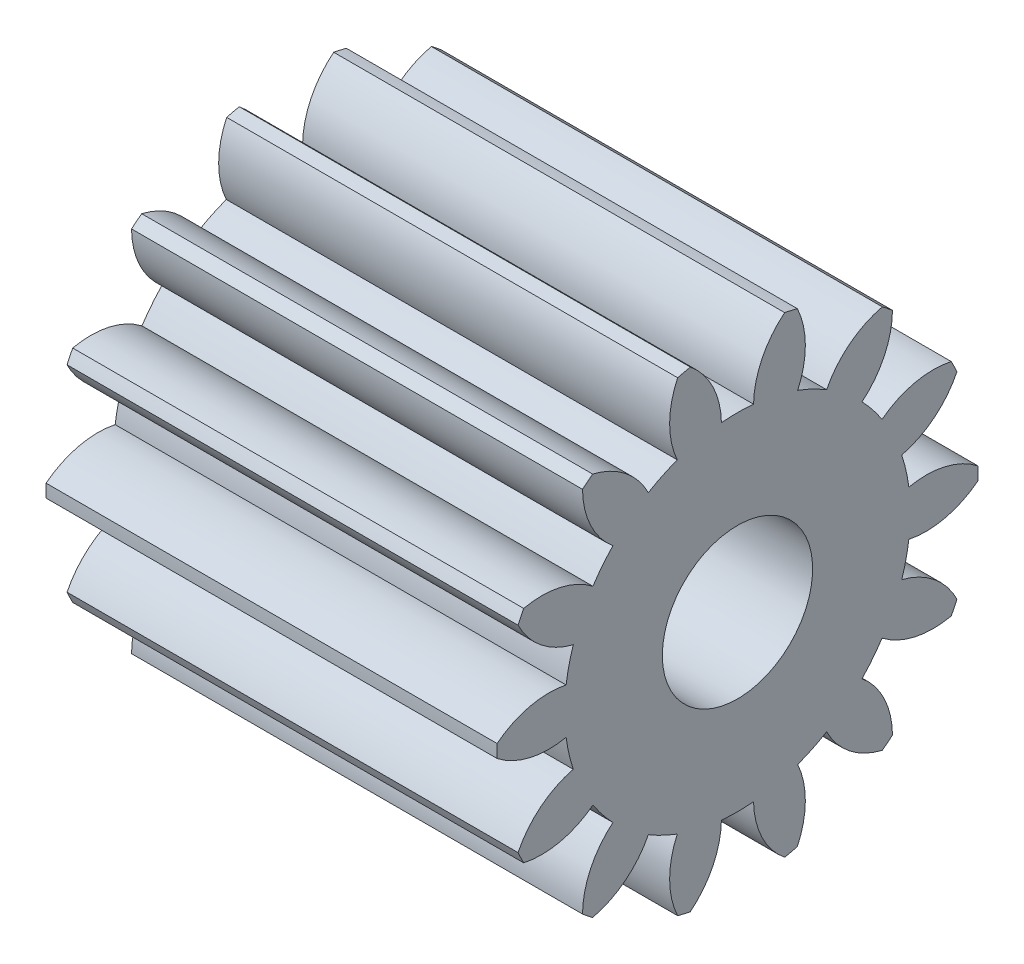
SolidWorks part; units mm, degrees
ref_plane "Plane1" through (0, 0, 0) normal (0, 0, 1) x (1, 0, 0)
ref_plane "Plane2" through (0, 0, 0) normal (0, 1, 0) x (1, 0, 0)
ref_plane "Plane3" through (0, 0, 0) normal (1, 0, 0) x (0, 0, -1)
sketch "HoldingSke" plane through (0, 0, 0) normal (0, 1, 0) x (1, 0, 0)
  line L0 (0, 0) -> (0.4851, -0.121)
  line L1 (-15, 0) -> (100, 0) construction
  line L2 (0, 0) -> (-2.1039, 2.3779)
  line L3 (0, 0) -> (-11.863, 4.5341)
  line L4 (0, 0) -> (8.3795, 2.0892)
  line L5 (0, 0) -> (-46.8476, -17.4728)
  line L6 (0, 0) -> (-24.8689, -16.7791)
  line L7 (-2.1039, 2.3779) -> (8.6586, 51.2059)
  line L8 (-76.2, 54.61) -> (-74.4, 54.61)
  line L9 (-71.009, 38.7566) -> (-53.1078, 45.2721)
  line L10 (-76.2, 71.12) -> (104.1128, 71.12)
  line L11 (0, 0) -> (-30, 0)
  line L12 (-76.2, 101.6) -> (-76.133, 101.6)
  line L13 (24.9733, 27.94) -> (52.9518, 28.4284)
  line L14 (24.9733, 27.94) -> (24.9743, 27.94)
  line L15 (24.9733, 27.94) -> (100.4006, 29.5858)
  line L16 (-63.627, -2) -> (-12.827, -2)
  circle A0 centre (0, 0) radius 5
  circle A1 centre (0, 0) radius 11.499
  circle A2 centre (0, 0) radius 37.5
  circle A3 centre (0, 0) radius 5
  dimension "MHD" = 22.998
  dimension "Hub_dia" = 75
  dimension "Bore" = 10
  dimension "MBD" = 10
  dimension "Num_teeth" = 14
  dimension "Pitch" = 0.5
  dimension "Overall_len" = 50
  dimension "Show_teeth" = 14
  dimension "Thickness" = 30
  dimension "OAL" = 50.0001
  dimension "T_dim" = 1.8
  dimension "Ap" = 20
  dimension "H" = 19.05
  dimension "Pitch_radius" = 180.3128
  dimension "Width" = 30
  dimension "Backlash" = 0.067
  dimension "Addendum_fac" = 1
  dimension "Dedendum_fac" = 1.25
  dimension "Clearance_fac" = 0.25
  dimension "Dedendum_add" = 0.001
  dimension "Module" = 2
sketch "BasProSke" plane through (0, 0, 0) normal (0, 1, 0) x (1, 0, 0)
  line L0 (-10, 0) -> (60, 0) construction
  line L1 (0, 0) -> (0, 16)
  line L2 (0, 0) -> (30, 0)
  line L3 (30, 0) -> (30, 16)
  line L4 (30, 16) -> (0, 16)
  dimension "Thickness" = 30
  dimension "Diameter" = 32
revolve "Base-Revolve" add sketch "BasProSke" angle 360 about L0
sketch "TooCutSke" plane through (0, 0, 0) normal (1, 0, 0) x (0, 0, -1)
  line L1 (0, 0) -> (0, 107) construction
  line L2 (0, 0) -> (-1.6846, 13.8983) construction
  line L3 (0, 0) -> (-6.1971, 27.1511) construction
  line L4 (-1.6846, 13.8983) -> (-3.0985, 13.5756) construction
  arc A0 (1.0679, 11.4493) -> (-1.0679, 11.4493) centre (0, 0) ccw
  arc A1 (3.1634, 15.7101) -> (-3.1634, 15.7101) centre (0, 0) ccw
  circle A2 centre (0, 0) radius 14 construction
  circle A3 centre (0, 0) radius 13.1557 construction
  arc A4 (-1.0679, 11.4493) -> (-3.1634, 15.7101) centre (-6.6668, 11.3413) ccw
  arc A5 (3.1634, 15.7101) -> (1.0679, 11.4493) centre (6.6668, 11.3413) ccw
  dimension "Root_dia" = 22.998
  dimension "Overcut_dia" = 32.0508
  dimension "Pitch_dia" = 28
  dimension "Base_dia" = 26.3114
  dimension "Flank_rad" = 5.6
  dimension "Half_ang" = 12.857
  dimension "Half_CT" = 1.4503
extrude "ToothCut" cut sketch "TooCutSke" along normal through all
fillet "Breaks" [suppressed] radius 0.04
fillet "RootFillets" [suppressed] radius 0.501
pattern_circular "TeethCuts" count 14 every 25.714 about axis through (-10, 0, 0) along (1, 0, 0) of "ToothCut", "RootFillets", "Breaks"
sketch "HubNeaOneSke" plane through (0, 0, 0) normal (-1, 0, 0) x (0, 0, 1)
  circle A0 centre (0, 0) radius 11.499
  dimension "Diameter" = 22.998
extrude "HubNearOne" [suppressed] add sketch "HubNeaOneSke" along normal blind 20.0001
sketch "HubNeaBotSke" plane through (0, 0, 0) normal (-1, 0, 0) x (0, 0, 1)
  circle A0 centre (0, 0) radius 11.499
  dimension "Diameter" = 22.998
extrude "HubNearBoth" [suppressed] add sketch "HubNeaBotSke" along normal blind 10
ref_plane "FarPln" through (30, 0, 0) normal (1, 0, 0) x (0, 0, -1)
sketch "HubFarSke" plane through (30, 0, 0) normal (1, 0, 0) x (0, 0, -1)
  circle A0 centre (0, 0) radius 11.499
  dimension "Diameter" = 22.998
extrude "HubFar" [suppressed] add sketch "HubFarSke" along normal blind 10
sketch "BorSke" plane through (0, 0, 0) normal (1, 0, 0) x (0, 0, -1)
  circle A0 centre (0, 0) radius 5
  dimension "Diameter" = 10
extrude "Bore" cut sketch "BorSke" along normal mid plane 100.0001
sketch "KeySke" plane through (0, 0, 0) normal (1, 0, 0) x (0, 0, -1)
  line L0 (-2, 0) -> (-2, 6.8)
  line L1 (-2, 6.8) -> (2, 6.8)
  line L2 (2, 6.8) -> (2, 0)
  line L3 (0, 0) -> (0, 34) construction
  line L4 (-2, 0) -> (2, 0)
  dimension "Offset" = 6.8
  dimension "Width" = 4
extrude "Keyway" [suppressed] cut sketch "KeySke" along normal mid plane 100.0001
pattern_circular "Keyway2" [suppressed] count 2 every 90 about axis through (-10, 0, 0) along (1, 0, 0)
equation "' \"Module@HoldingSke\" = 6.35"
equation "' \"Num_teeth@HoldingSke\" = 12"
equation "' \"Ap@HoldingSke\" =  20"
equation "' \"Ap@HoldingSke\" = 20"
equation "' \"Width@HoldingSke\" = 0.5 * 25.4"
equation "' \"Hub_dia@HoldingSke\"= 1 * 25.4"
equation "' \"Hub_dia@HoldingSke\" = 1 * 25.4"
equation "' \"Overall_len@HoldingSke\" = 1.0 * 25.4"
equation "' \"Bore@HoldingSke\" = 0.75 * 25.4"
equation "' \"T_dim@HoldingSke\" = 0.1 * 25.4"
equation "' \"Width@KeySke\" = 0.25 * 25.4"
equation "' \"Show_teeth@HoldingSke\" = 13"
equation "' \"Backlash@HoldingSke\" = 0.009 * 25.4"
equation "' \"Addendum_fac@HoldingSke\" = 1.0"
equation "' \"Dedendum_fac@HoldingSke\" = 1.25"
equation "' \"Dedendum_add@HoldingSke\" = 0.00005 * 25.4"
equation "' \"Clearance_fac@HoldingSke\" = 0.25"
equation "\"Pitch@HoldingSke\" = 1 / \"Module@HoldingSke\""
equation "\"Overcut_dia@TooCutSke\" = (\"Num_teeth@HoldingSke\" + 2 * \"Addendum_fac@HoldingSke\") / \"Pitch@HoldingSke\" + 0.002 * 25.4"
equation "\"Pitch_dia@TooCutSke\" = \"Num_teeth@HoldingSke\" / \"Pitch@HoldingSke\""
equation "\"Base_dia@TooCutSke\" = \"Num_teeth@HoldingSke\" / \"Pitch@HoldingSke\" * cos((\"Ap@HoldingSke\"  * 3.14159265 / 180))"
equation "\"Root_dia@TooCutSke\" = (\"Num_teeth@HoldingSke\" + 2) / \"Pitch@HoldingSke\" - 2 * (\"Addendum_fac@HoldingSke\" + \"Dedendum_fac@HoldingSke\") / \"Pitch@HoldingSke\" - \"Dedendum_add@HoldingSke\" * 2"
equation "\"Half_ang@TooCutSke\" = 180 / \"Num_teeth@HoldingSke\""
equation "\"Half_CT@TooCutSke\" = \"Num_teeth@HoldingSke\" / \"Pitch@HoldingSke\" * sin((3.14159265 / 2 / \"Num_teeth@HoldingSke\")) / 2 - 7 * \"Backlash@HoldingSke\" / 4"
equation "\"Flank_rad@TooCutSke\" = \"Num_teeth@HoldingSke\" / \"Pitch@HoldingSke\" / 5"
equation "\"Radius@RootFillets\" = \"Clearance_fac@HoldingSke\" / \"Pitch@HoldingSke\" + \"Dedendum_add@HoldingSke\""
equation "\"Break_rad@Breaks\" = 0.02 / \"Pitch@HoldingSke\""
equation "\"Thickness@HoldingSke\" = \"Width@HoldingSke\""
equation "\"OAL@HoldingSke\" = \"Thickness@HoldingSke\""
equation "\"MHD@HoldingSke\" = (\"Num_teeth@HoldingSke\" + 2) / \"Pitch@HoldingSke\" - 2 * (\"Addendum_fac@HoldingSke\" + \"Dedendum_fac@HoldingSke\")  / \"Pitch@HoldingSke\" - \"Dedendum_add@HoldingSke\" * 2"
equation "\"MBD@HoldingSke\" = (\"Num_teeth@HoldingSke\" + 2) / \"Pitch@HoldingSke\" - 2 * (\"Addendum_fac@HoldingSke\" + \"Dedendum_fac@HoldingSke\")  / \"Pitch@HoldingSke\" - \"Dedendum_add@HoldingSke\" * 2 - 0.002 * 25.4"
equation "\"MHD@HoldingSke\" = ((sgn( \"MHD@HoldingSke\" - \"Hub_dia@HoldingSke\" )-1)*( \"MHD@HoldingSke\" - \"Hub_dia@HoldingSke\" ))/-2+ \"Hub_dia@HoldingSke\""
equation "\"MBD@HoldingSke\" = ((sgn( \"MBD@HoldingSke\" - \"Bore@HoldingSke\" )-1)*( \"MBD@HoldingSke\" - \"Bore@HoldingSke\" ))/-2+ \"Bore@HoldingSke\""
equation "\"OAL@HoldingSke\" = ((sgn( \"OAL@HoldingSke\" - \"Overall_len@HoldingSke\" )+1)*( \"OAL@HoldingSke\" - \"Overall_len@HoldingSke\" ))/2 + \"Overall_len@HoldingSke\" + 0.000002 * 25.4"
equation "\"Num_teeth@TeethCuts\" = int( \"Show_teeth@HoldingSke\" ) + 1"
equation "\"Num_teeth@TeethCuts\" = ((sgn( \"Num_teeth@TeethCuts\" - \"Num_teeth@HoldingSke\" )-1)*( \"Num_teeth@TeethCuts\" - \"Num_teeth@HoldingSke\" ))/-2+ \"Num_teeth@HoldingSke\""
equation "\"Num_teeth@TeethCuts\" = ((sgn( \"Num_teeth@TeethCuts\" - 2.0)+1)*( \"Num_teeth@TeethCuts\" - 2.0))/2 +2.0"
equation "\"Angle@TeethCuts\" = 360.0 / \"Num_teeth@HoldingSke\""
equation "\"Diameter@BasProSke\" = (\"Num_teeth@HoldingSke\" + 2 * \"Addendum_fac@HoldingSke\") / \"Pitch@HoldingSke\""
equation "\"Thickness@BasProSke\"  = \"Thickness@HoldingSke\""
equation "' \"Fillet_rad@BasProSke\" =  \"Thickness@HoldingSke\" * 0.05"
equation "' \"Fillet_rad@BasProSke\" = \"Thickness@HoldingSke\" * 0.05"
equation "\"MHD@HoldingSke\" = ((sgn( \"MHD@HoldingSke\" - \"Root_dia@TooCutSke\" )-1)*( \"MHD@HoldingSke\" - \"Root_dia@TooCutSke\" ))/-2+ \"Root_dia@TooCutSke\""
equation "\"Diameter@HubNeaOneSke\" = \"MHD@HoldingSke\""
equation "\"Length@HubNearOne\" = \"OAL@HoldingSke\" - \"Thickness@BasProSke\""
equation "\"Diameter@HubNeaBotSke\" = \"MHD@HoldingSke\""
equation "\"Length@HubNearBoth\" = ( \"OAL@HoldingSke\" - \"Thickness@BasProSke\" ) / 2.0"
equation "\"Thickness@FarPln\" = \"Thickness@BasProSke\""
equation "\"Diameter@HubFarSke\" = \"MHD@HoldingSke\""
equation "\"Length@HubFar\" = ( \"OAL@HoldingSke\" - \"Thickness@BasProSke\" ) / 2.0"
equation "\"Diameter@BorSke\" = \"MBD@HoldingSke\""
equation "\"D1@Bore\" = \"OAL@HoldingSke\" * 2.0"
equation "\"D1@Keyway\" = \"OAL@HoldingSke\" * 2.0"
equation "\"Offset@KeySke\" = \"T_dim@HoldingSke\" + \"MBD@HoldingSke\" / 2.0"
